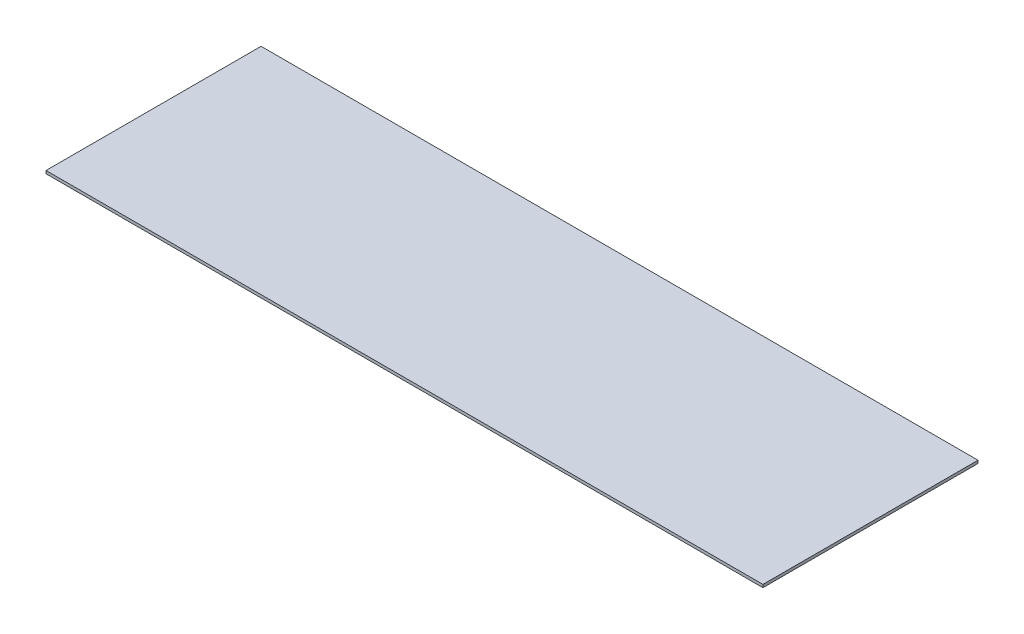
SolidWorks part; units mm, degrees
material "Glas"
ref_plane "Ebene vorne" through (0, 0, 0) normal (0, 0, 1) x (1, 0, 0)
ref_plane "Ebene oben" through (0, 0, 0) normal (0, 1, 0) x (1, 0, 0)
ref_plane "Ebene rechts" through (0, 0, 0) normal (1, 0, 0) x (0, 0, -1)
sketch "Skizze1" plane through (0, 0, 0) normal (0, 0, 1) x (1, 0, 0)
  line L0 (500, 0) -> (-500, 0)
  line L1 (500, 4) -> (-500, 4)
  line L2 (-500, 4) -> (-500, 0)
  line L3 (500, 0) -> (500, 4)
  point P4 (0, 0)
  point P8 (0, 4)
  dimension "D1" = 4
  dimension "D2" = 1000
extrude "Aufsatz-Linear austragen1" add sketch "Skizze1" along normal blind 300
equation "\"wall_thickness\"= 4mm"
equation "\"wall_height\"= 300"
equation "\"D1@Skizze1\"=\"wall_thickness\""
equation "\"D1@Aufsatz-Linear austragen1\"=\"wall_height\""
equation "\"edge_length\"= 800mm"
equation "\"coldplate_circumference\"= 4*\"edge_length\""
equation "\"L-profile_width\"= 20mm"
equation "\"L-profile_thickness\"= 1.5mm"
equation "\"extrusion_width\"= 40mm"
equation "\"D2@Skizze1\"=\"edge_length\" + 200"
